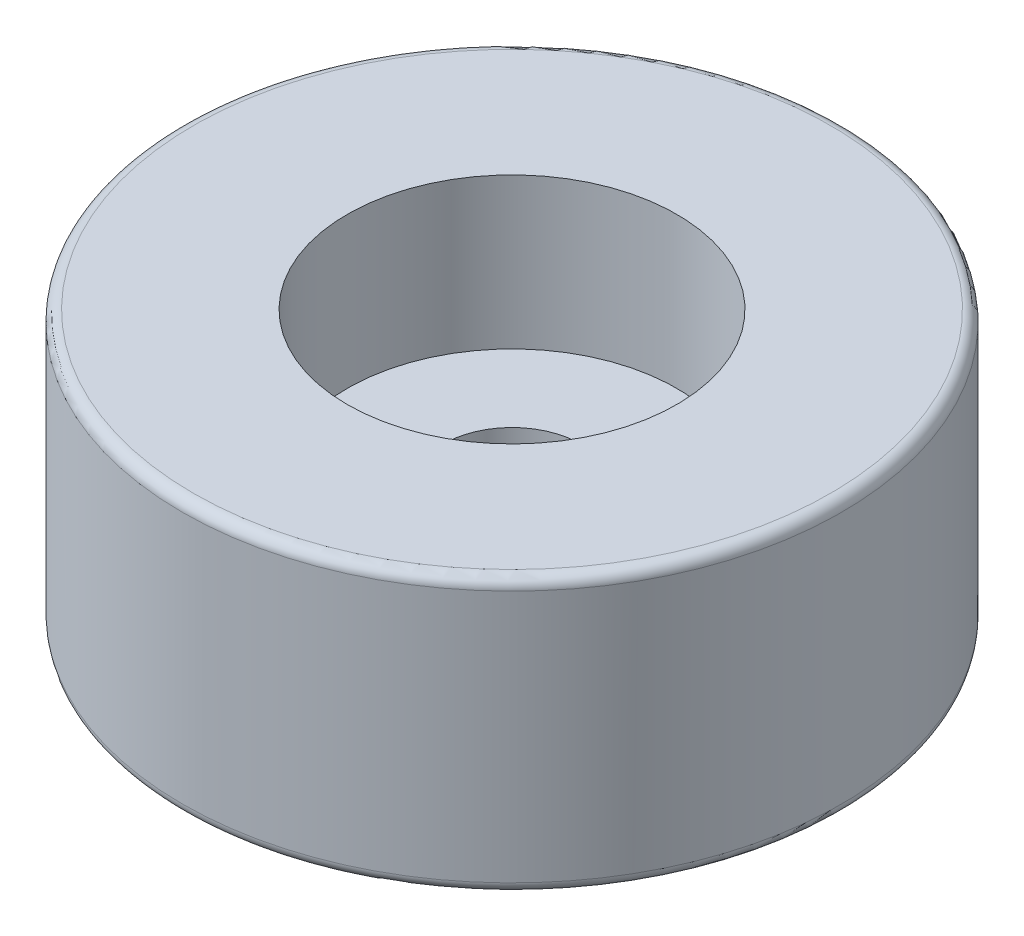
SolidWorks part; units mm, degrees
ref_plane "Front Plane" through (0, 0, 0) normal (0, 0, 1) x (1, 0, 0)
ref_plane "Top Plane" through (0, 0, 0) normal (0, 1, 0) x (1, 0, 0)
ref_plane "Right Plane" through (0, 0, 0) normal (1, 0, 0) x (0, 0, -1)
sketch "Sketch1" plane through (0, 0, 0) normal (0, 0, 1) x (1, 0, 0)
  line L0 (0, 5.0169) -> (0, -10.8581) construction
  line L1 (-19.05, 5.0169) -> (-19.05, -10.8581)
  line L2 (-9.525, 5.0169) -> (-9.525, -3.6953)
  line L3 (-3.9624, -3.6953) -> (-3.9624, -10.8581)
  line L4 (-19.05, 5.0169) -> (-9.525, 5.0169)
  line L5 (-9.525, -3.6953) -> (-3.9624, -3.6953)
  line L6 (-19.05, -3.6953) -> (-9.525, -3.6953) construction
  line L7 (-19.05, -10.8581) -> (-3.9624, -10.8581)
  dimension "D1" = 19.05
  dimension "D2" = 7.9248
  dimension "D3" = 38.1
  dimension "D4" = 15.875
  dimension "D5" = 8.7122
revolve "Revolve1" add sketch "Sketch1" angle 360 about L0
fillet "Fillet1" radius 0.635 2 edges at (0, 5.0169, 19.05) (0, -10.8581, 19.05)
